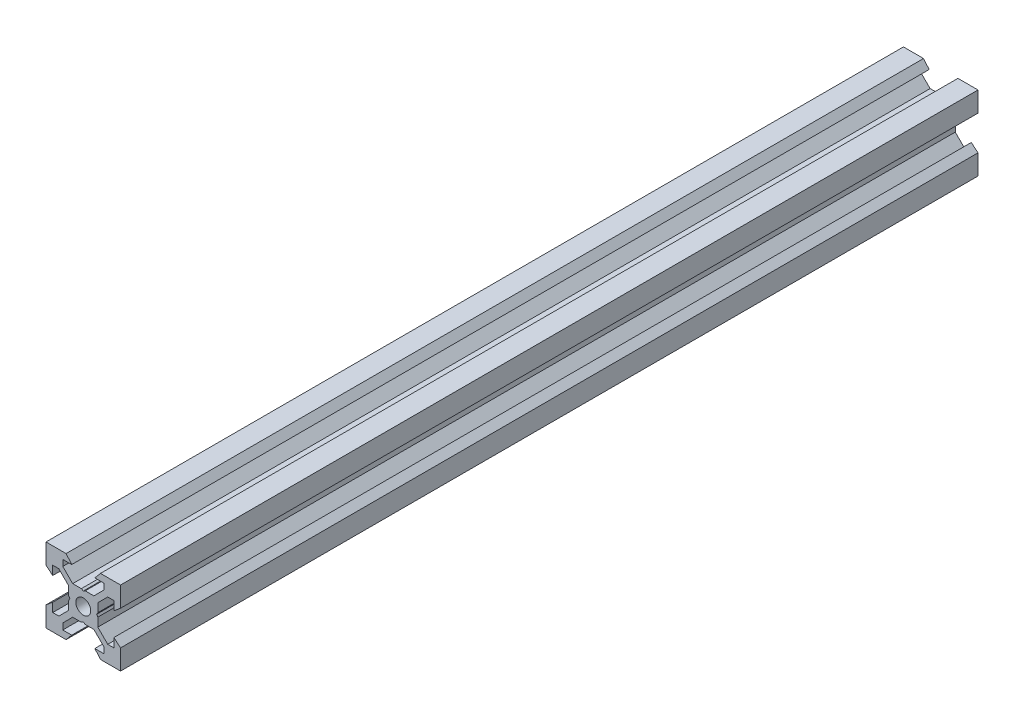
SolidWorks part; units mm, degrees
ref_plane "Front Plane" through (0, 0, 0) normal (0, 0, 1) x (1, 0, 0)
ref_plane "Top Plane" through (0, 0, 0) normal (0, 1, 0) x (1, 0, 0)
ref_plane "Right Plane" through (0, 0, 0) normal (1, 0, 0) x (0, 0, -1)
sketch "Sketch1" plane through (0, 0, 0) normal (0, 0, 1) x (1, 0, 0)
  line L0 (10, 10) -> (4.6104, 10) construction
  line L1 (10, 10) -> (10, 4.6104) construction
  line L2 (10, -10) -> (10, -4.6104) construction
  line L3 (10, -10) -> (4.6104, -10) construction
  line L4 (10, 10) -> (10, 4.6104)
  line L5 (6.5607, 5.5) -> (8.2, 5.5)
  line L6 (5.5, 8.2) -> (5.5, 6.5607)
  line L7 (10, 10) -> (4.6104, 10)
  line L8 (10, 10) -> (10, 4.6104)
  line L9 (6.5607, 5.5) -> (3.9, 2.8393)
  line L10 (5.5, 6.5607) -> (2.8393, 3.9)
  line L11 (10, 4.6104) -> (8.2, 3.1)
  line L12 (4.6104, 10) -> (3.1, 8.2)
  line L13 (8.2, 3.1) -> (8.2, 5.5)
  line L14 (3.1, 8.2) -> (5.5, 8.2)
  line L15 (-6.5607, 5.5) -> (-8.2, 5.5)
  line L16 (6.5607, -5.5) -> (8.2, -5.5)
  line L17 (3.1, -8.2) -> (5.5, -8.2)
  line L18 (8.2, -3.1) -> (8.2, -5.5)
  line L19 (4.6104, -10) -> (3.1, -8.2)
  line L20 (10, -4.6104) -> (8.2, -3.1)
  line L21 (0.5196, -3.9) -> (0, -3.6)
  line L22 (0.5196, 3.9) -> (0, 3.6)
  line L23 (3.6, 0) -> (3.9, -0.5196)
  line L24 (3.9, 0.5196) -> (3.6, 0)
  line L25 (3.9, 0.5196) -> (3.9, 2.8393)
  line L26 (2.8393, 3.9) -> (0.5196, 3.9)
  line L27 (3.9, -2.8393) -> (3.9, -0.5196)
  line L28 (2.8393, -3.9) -> (0.5196, -3.9)
  line L29 (5.5, -6.5607) -> (2.8393, -3.9)
  line L30 (6.5607, -5.5) -> (3.9, -2.8393)
  line L31 (10, -10) -> (10, -4.6104)
  line L32 (10, -10) -> (4.6104, -10)
  line L33 (5.5, -8.2) -> (5.5, -6.5607)
  line L34 (-6.5607, -5.5) -> (-8.2, -5.5)
  line L35 (10, -10) -> (10, -4.6104)
  line L36 (0, 0) -> (0, 8.2) construction
  line L37 (-10, -10) -> (-4.6104, -10) construction
  line L38 (-10, -10) -> (-10, -4.6104) construction
  line L39 (-10, 10) -> (-10, 4.6104) construction
  line L40 (-10, 10) -> (-4.6104, 10) construction
  line L41 (-10, -10) -> (-10, -4.6104)
  line L43 (-5.5, -8.2) -> (-5.5, -6.5607)
  line L44 (-10, -10) -> (-4.6104, -10)
  line L45 (-10, -10) -> (-10, -4.6104)
  line L46 (-6.5607, -5.5) -> (-3.9, -2.8393)
  line L47 (-5.5, -6.5607) -> (-2.8393, -3.9)
  line L48 (-2.8393, -3.9) -> (-0.5196, -3.9)
  line L49 (-3.9, -2.8393) -> (-3.9, -0.5196)
  line L50 (-2.8393, 3.9) -> (-0.5196, 3.9)
  line L51 (-3.9, 0.5196) -> (-3.9, 2.8393)
  line L52 (-3.9, 0.5196) -> (-3.6, 0)
  line L53 (-3.6, 0) -> (-3.9, -0.5196)
  line L54 (-0.5196, 3.9) -> (0, 3.6)
  line L55 (-0.5196, -3.9) -> (0, -3.6)
  line L56 (-10, -4.6104) -> (-8.2, -3.1)
  line L57 (-4.6104, -10) -> (-3.1, -8.2)
  line L58 (-8.2, -3.1) -> (-8.2, -5.5)
  line L59 (-3.1, -8.2) -> (-5.5, -8.2)
  line L60 (-10, -10) -> (10, -10) construction
  line L61 (-10, -10) -> (-10, 10) construction
  line L62 (-3.1, 8.2) -> (-5.5, 8.2)
  line L63 (-8.2, 3.1) -> (-8.2, 5.5)
  line L64 (-4.6104, 10) -> (-3.1, 8.2)
  line L65 (-10, 4.6104) -> (-8.2, 3.1)
  line L66 (-5.5, 6.5607) -> (-2.8393, 3.9)
  line L67 (-6.5607, 5.5) -> (-3.9, 2.8393)
  line L68 (-10, 10) -> (-10, 4.6104)
  line L69 (-10, 10) -> (-4.6104, 10)
  line L70 (-5.5, 8.2) -> (-5.5, 6.5607)
  line L71 (-10, 10) -> (10, 10) construction
  line L72 (-10, 10) -> (-10, 4.6104)
  line L73 (10, -10) -> (10, 10) construction
  line L74 (-10, -10) -> (10, 10) construction
  line L75 (-10, 10) -> (10, -10) construction
  circle A0 centre (0, 0) radius 2
  dimension "D7" = 4
  dimension "D1" = 20
  dimension "D2" = 5.3896
  dimension "D3" = 4.5
  dimension "D4" = 50
  dimension "D5" = 1.8
  dimension "D6" = 1.5104
  dimension "D8" = 5.5
  dimension "D9" = 120
  dimension "D10" = 0.3
  dimension "D11" = 2.3197
  dimension "D12" = 7.8
  dimension "D13" = 7.8
  dimension "D14" = 1.5
  dimension "D15" = 2.6607
extrude "Boss-Extrude1" add sketch "Sketch1" along normal mid plane 230 contours L70 L62 L64 L69 L68 L65 L63 L15 L67 L51 L52 L53 L49 L46 L34 L58 L56 L41 L44 L57 L59 L43 L47 L48 L55 L21 L28 L29 L33 L17 L19 L32 L31 L20 L18 L16 L30 L27 L23 L24 L25 L9 L5 L13 L11 L4 L7 L12 L14 L6 L10
